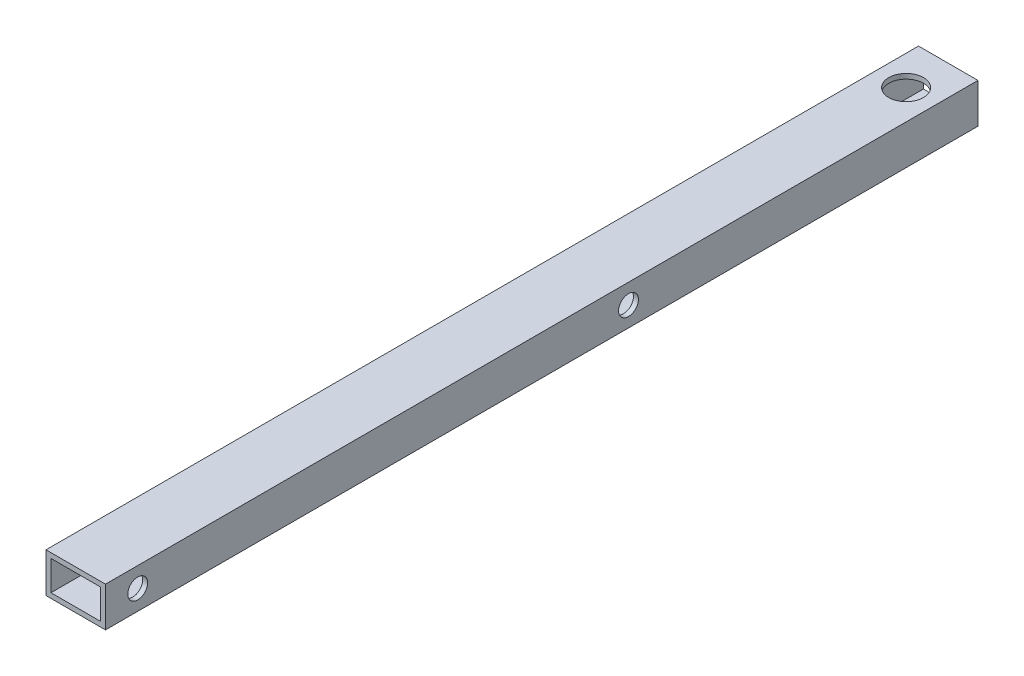
SolidWorks part; units mm, degrees
ref_plane "Front Plane" through (0, 0, 0) normal (0, 0, 1) x (1, 0, 0)
ref_plane "Top Plane" through (0, 0, 0) normal (0, 1, 0) x (1, 0, 0)
ref_plane "Right Plane" through (0, 0, 0) normal (1, 0, 0) x (0, 0, -1)
sketch "Sketch1" plane through (0, 0, 0) normal (0, 0, 1) x (1, 0, 0)
  line L1 (-19.05, 12.7) -> (19.05, 12.7)
  line L2 (-19.05, 12.7) -> (-19.05, -12.7)
  line L3 (-19.05, -12.7) -> (19.05, -12.7)
  line L4 (19.05, 12.7) -> (19.05, -12.7)
  line L5 (-19.05, 12.7) -> (19.05, -12.7) construction
  line L6 (-19.05, -12.7) -> (19.05, 12.7) construction
  line L7 (-15.875, 9.525) -> (15.875, 9.525)
  line L8 (-15.875, 9.525) -> (-15.875, -9.525)
  line L9 (-15.875, -9.525) -> (15.875, -9.525)
  line L10 (15.875, 9.525) -> (15.875, -9.525)
  line L11 (-15.875, 9.525) -> (15.875, -9.525) construction
  line L12 (-15.875, -9.525) -> (15.875, 9.525) construction
  point P0 (0, 0)
  point P6 (0, 0)
  dimension "D1" = 25.4
  dimension "D2" = 38.1
  dimension "D3" = 31.75
  dimension "D4" = 19.05
extrude "Boss-Extrude1" add sketch "Sketch1" along normal blind 558.8
sketch "Sketch2" plane through (0, 12.7, 0) normal (0, 1, 0) x (1, 0, 0)
  line L0 (19.05, 0) -> (-19.05, 0) construction
  circle A0 centre (0, -26.9875) radius 11.1125
  point P21 (0, -26.9875)
  dimension "D1" = 22.225
  dimension "D2" = 26.9875
extrude "Cut-Extrude1" cut sketch "Sketch2" against normal up to surface (25.4 mm away) up to face at (0, -12.7, 279.4)
sketch "Sketch3" plane through (-19.05, 0, 0) normal (-1, 0, 0) x (0, 0, 1)
  line L0 (558.8, 12.7) -> (558.8, -12.7) construction
  circle A0 centre (538.1625, 0) radius 3.175
  circle A1 centre (223.8375, 0) radius 3.175
  dimension "D1" = 6.35
  dimension "D3" = 6.35
  dimension "D4" = 334.9625
  dimension "D2" = 20.6375
extrude "Cut-Extrude2" cut sketch "Sketch3" against normal up to surface (3.175 mm away) up to face at (-15.875, 0, 279.4)
sketch "Sketch4" plane through (19.05, 0, 0) normal (1, 0, 0) x (0, 0, -1)
  circle A0 centre (-538.1625, 0) radius 6.35
  circle A1 centre (-538.1625, 0) radius 3.175 construction
  circle A2 centre (-223.8375, 0) radius 6.35
  circle A3 centre (-223.8375, 0) radius 3.175 construction
  dimension "D1" = 12.7
  dimension "D2" = 0
  dimension "D3" = 12.7
  dimension "D4" = 0
extrude "Cut-Extrude3" cut sketch "Sketch4" against normal up to surface (3.175 mm away) up to face at (15.875, 0, 279.4)
